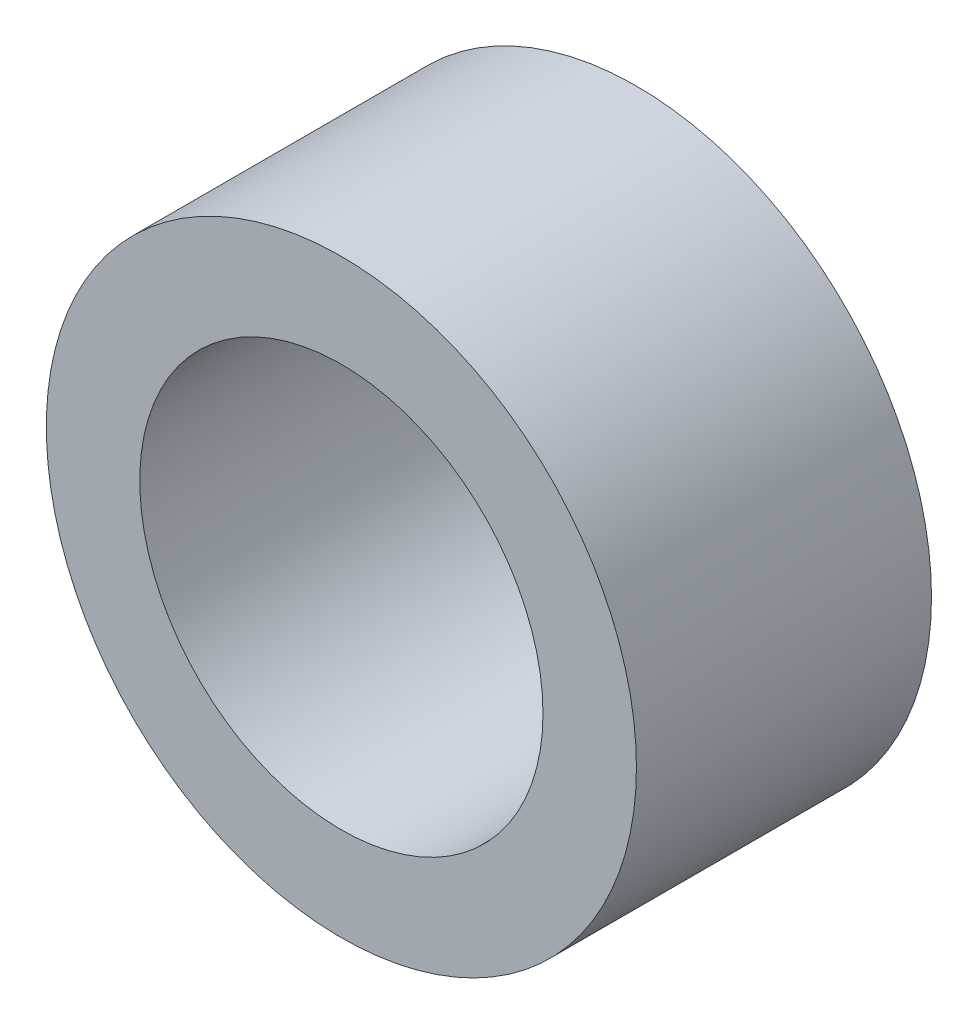
SolidWorks part; units mm, degrees
ref_plane "Front Plane" through (0, 0, 0) normal (0, 0, 1) x (1, 0, 0)
ref_plane "Top Plane" through (0, 0, 0) normal (0, 1, 0) x (1, 0, 0)
ref_plane "Right Plane" through (0, 0, 0) normal (1, 0, 0) x (0, 0, -1)
sketch "Sketch0" plane through (0, 0, 0) normal (0, 1, 0) x (0, 0, -1)
  line L0 (-3, 0) -> (3, 0) construction
  line L1 (-3, 0) -> (-3, 6) construction
  line L2 (-3, 6) -> (3, 6) construction
  line L3 (3, 6) -> (3, 0) construction
  line L4 (-3, -6) -> (-3, 6) construction
  line L6 (-3, 4.1) -> (-3, -4.1) construction
  point P2 (0, 0)
  point P8 (-3, 0)
  point P11 (-3, 0)
  point P12 (-3, 4.1)
  point P13 (-3, -4.1)
  point P15 (3, 6)
  point P17 (-3, 6)
  dimension "Length" = 6
  dimension "OD" = 12
  dimension "ID" = 8.2
sketch "Sketch1" plane through (0, 0, 0) normal (1, 0, 0) x (0, 0, -1)
  line L0 (3, 0) -> (-3, 0) construction
  line L1 (-3, 0) -> (3, 0)
  line L2 (-3, 0) -> (-3, 6)
  line L3 (-3, 6) -> (3, 6)
  line L4 (3, 0) -> (3, 6)
  line L5 (-3, 0) -> (3, 6) construction
  line L6 (-3, 6) -> (3, 0) construction
  point P0 (-3, 0)
  dimension "D1" = 12
  dimension "Length" = 6
sketch "Sketch5" plane through (0, 0, 0) normal (0, 1, 0) x (0, 0, -1)
  line L1 (-3, 6) -> (3, 6)
  line L2 (-3, 6) -> (-3, 0)
  line L3 (-3, 0) -> (3, 0)
  line L4 (3, 6) -> (3, 0)
revolve "Revolve1" add sketch "Sketch5" angle 360 about L0
sketch "Sketch7" plane through (0, 0, 3) normal (0, 0, 1) x (1, 0, 0)
  circle A0 centre (0, 0) radius 4.1
extrude "Cut-Extrude1" cut sketch "Sketch7" against normal through all
equation "\"D1@Sketch1\"=\"od@sketch0\""
